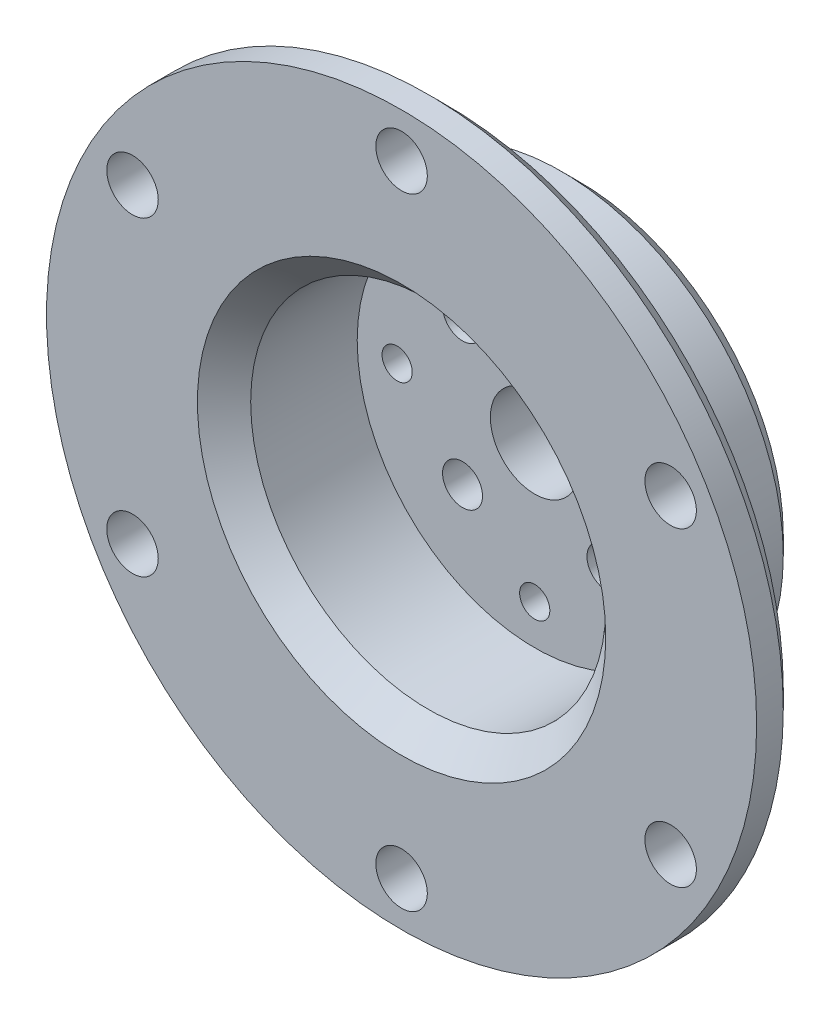
SolidWorks part; units mm, degrees
ref_plane "前视基准面" through (0, 0, 0) normal (0, 0, 1) x (1, 0, 0)
ref_plane "上视基准面" through (0, 0, 0) normal (0, 1, 0) x (1, 0, 0)
ref_plane "右视基准面" through (0, 0, 0) normal (1, 0, 0) x (0, 0, -1)
sketch "草图1" plane through (0, 0, 0) normal (0, 1, 0) x (1, 0, 0)
  line L0 (38, -15) -> (25, -15)
  line L2 (23, -20) -> (40, -20)
  line L3 (40, -20) -> (40, -17)
  line L4 (20, -17) -> (23, -20)
  line L5 (0, 0) -> (0, -5)
  line L6 (0, -5) -> (20, -5)
  line L7 (20, -5) -> (20, -17)
  line L9 (25, -15) -> (25, -2)
  line L10 (23, 0) -> (0, 0)
  line L12 (25, -2) -> (23, 0)
  line L13 (40, -17) -> (38, -15)
  point P0 (40, -15)
  point P10 (20, -20)
  point P12 (25, 0)
  dimension "D2" = 25
  dimension "D3" = 5
  dimension "D4" = 5
  dimension "D5" = 40
  dimension "D6" = 15
  dimension "D7" = 5
revolve "旋转1" add sketch "草图1" angle 360 about L5
sketch "草图9" plane through (0, 0, 0) normal (0, 0, -1) x (-1, 0, 0)
  line L1 (-8.1317, -8.1317) -> (8.1317, -8.1317) construction
  line L2 (-8.1317, -8.1317) -> (-8.1317, 8.1317) construction
  line L3 (-8.1317, 8.1317) -> (8.1317, 8.1317) construction
  line L4 (8.1317, -8.1317) -> (8.1317, 8.1317) construction
  line L5 (-8.1317, -8.1317) -> (8.1317, 8.1317) construction
  line L6 (-8.1317, 8.1317) -> (8.1317, -8.1317) construction
  line L7 (15.5, 0) -> (0, 15.5) construction
  line L8 (0, 15.5) -> (-15.5, 0) construction
  line L9 (-15.5, 0) -> (0, -15.5) construction
  line L10 (0, -15.5) -> (15.5, 0) construction
  circle A0 centre (-8.1317, 8.1317) radius 2.25
  circle A1 centre (8.1317, 8.1317) radius 2.25
  circle A2 centre (8.1317, -8.1317) radius 2.25
  circle A3 centre (-8.1317, -8.1317) radius 2.25
  circle A4 centre (0, 0) radius 5
  circle A5 centre (0, 0) radius 11.5 construction
  circle A6 centre (0, 0) radius 15.5 construction
  circle A7 centre (0, 15.5) radius 1.7
  circle A8 centre (-15.5, 0) radius 1.7
  circle A9 centre (0, -15.5) radius 1.7
  circle A10 centre (15.5, 0) radius 1.7
  point P0 (0, 0)
  dimension "D2" = 4.5
  dimension "D3" = 10
  dimension "D1" = 23
  dimension "D4" = 31
  dimension "D5" = 3.4
  dimension "D6" = 45
extrude "切除-拉伸1" cut sketch "草图9" against normal up to next
sketch "草图11" plane through (0, 0, 20) normal (0, 0, 1) x (1, 0, 0)
  line L1 (0, 35) -> (-30.3109, 17.5) construction
  line L2 (-30.3109, 17.5) -> (-30.3109, -17.5) construction
  line L3 (-30.3109, -17.5) -> (0, -35) construction
  line L4 (0, -35) -> (30.3109, -17.5) construction
  line L5 (30.3109, -17.5) -> (30.3109, 17.5) construction
  line L6 (30.3109, 17.5) -> (0, 35) construction
  circle A0 centre (0, 0) radius 30.3109 construction
  circle A1 centre (0, 35) radius 2.9
  circle A2 centre (-30.3109, 17.5) radius 2.9
  circle A3 centre (-30.3109, -17.5) radius 2.9
  circle A4 centre (0, -35) radius 2.9
  circle A5 centre (30.3109, -17.5) radius 2.9
  circle A6 centre (30.3109, 17.5) radius 2.9
  dimension "D1" = 70
  dimension "D2" = 5.8
extrude "切除-拉伸2" cut sketch "草图11" against normal blind 10
